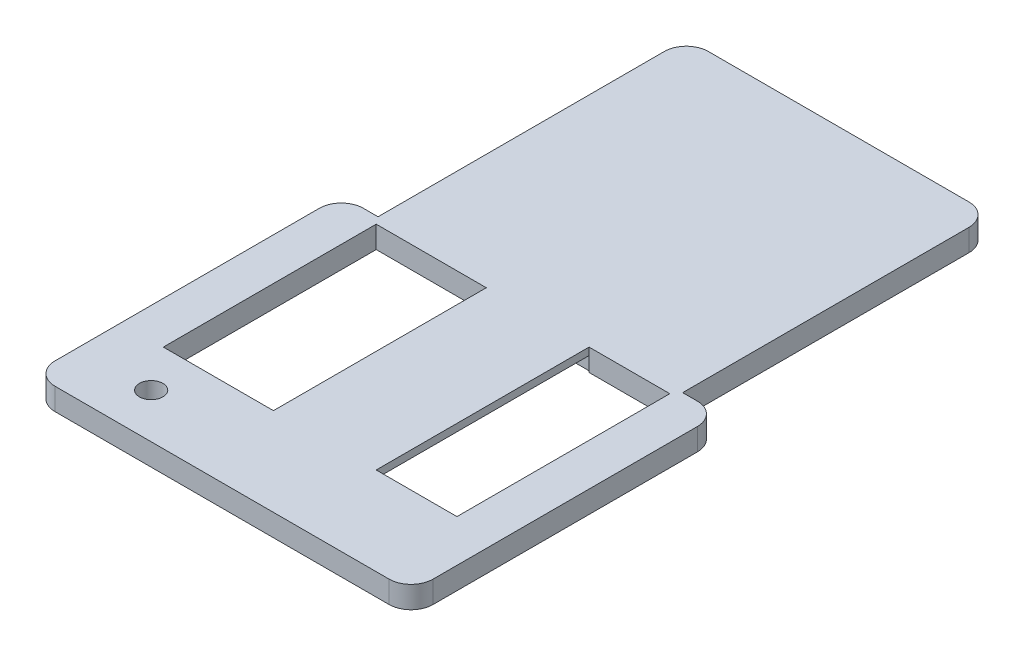
SolidWorks part; units mm, degrees
ref_plane "Front Plane" through (0, 0, 0) normal (0, 0, 1) x (1, 0, 0)
ref_plane "Top Plane" through (0, 0, 0) normal (0, 1, 0) x (1, 0, 0)
ref_plane "Right Plane" through (0, 0, 0) normal (1, 0, 0) x (0, 0, -1)
sketch "Sketch1" plane through (0, 0, 0) normal (0, 1, 0) x (1, 0, 0)
  line L0 (-20.75, 42) -> (-20.75, 0)
  line L1 (-20.75, 0) -> (-25.75, 0)
  line L2 (-25.75, 0) -> (-25.75, -42)
  line L3 (-25.75, -42) -> (25.75, -42)
  line L4 (25.75, -42) -> (25.75, 0)
  line L5 (25.75, 0) -> (20.75, 0)
  line L6 (20.75, 0) -> (20.75, 42)
  line L7 (20.75, 42) -> (-20.75, 42)
  line L8 (0, 42) -> (0, -42) construction
  dimension "D1" = 41.5
  dimension "D2" = 42
  dimension "D3" = 84
  dimension "D4" = 51.5
extrude "Boss-Extrude1" add sketch "Sketch1" along normal blind 3
fillet "Fillet1" radius 3 6 edges at (25.75, 1.5, 0) (25.75, 1.5, 42) (-25.75, 1.5, 42) (-25.75, 1.5, 0) (-20.75, 1.5, -42) (20.75, 1.5, -42)
sketch "Sketch2" plane through (0, 3, 0) normal (0, 1, 0) x (1, 0, 0)
  line L1 (-20, -1) -> (-5, -1)
  line L2 (-20, -1) -> (-20, -30)
  line L3 (-20, -30) -> (-5, -30)
  line L4 (-5, -1) -> (-5, -30)
  line L5 (-20, -1) -> (-5, -30) construction
  line L6 (-20, -30) -> (-5, -1) construction
  line L7 (20, -30) -> (9, -30)
  line L8 (20, -30) -> (20, -1)
  line L9 (20, -1) -> (9, -1)
  line L10 (9, -30) -> (9, -1)
  line L11 (20, -30) -> (9, -1) construction
  line L12 (20, -1) -> (9, -30) construction
  line L13 (-20, -15.5) -> (-25.75, -15.5) construction
  line L14 (-25.75, -3) -> (-25.75, -39) construction
  line L15 (20, -15.5) -> (25.75, -15.5) construction
  line L16 (25.75, -39) -> (25.75, -3) construction
  line L17 (-20.75, 0) -> (-22.75, 0) construction
  line L18 (-15.75, -30) -> (-15.75, -35.9074) construction
  line L19 (-15.75, -35.9074) -> (-15.75, -42) construction
  line L20 (-22.75, -42) -> (22.75, -42) construction
  line L21 (-25.75, -3) -> (-25.75, -39) construction
  circle A0 centre (-15.75, -35.9074) radius 1.6
  point P0 (-12.5, -15.5)
  point P5 (14.5, -15.5)
  point P22 (-21.75, 0)
  dimension "D6" = 3.2
  dimension "D1" = 29
  dimension "D2" = 15
  dimension "D3" = 11
  dimension "D4" = 1
  dimension "D5" = 14
  dimension "D7" = 10
extrude "Cut-Extrude1" cut sketch "Sketch2" against normal blind 3
sketch "Sketch3" plane through (0, 0, 0) normal (0, -1, 0) x (1, 0, 0)
  line L0 (10, -26) -> (10, -18)
  line L1 (10, -18) -> (2, -22)
  line L2 (2, -22) -> (10, -26)
  line L3 (-7, -22) -> (10, -22) construction
  line L4 (-4, -18) -> (-2, -18)
  line L5 (-4, -18) -> (-4, -26)
  line L6 (-4, -26) -> (-2, -26)
  line L7 (-2, -18) -> (-2, -26)
  line L8 (-4, -18) -> (-2, -26) construction
  line L9 (-4, -26) -> (-2, -18) construction
  line L10 (-8, -18) -> (-6, -18)
  line L11 (-8, -18) -> (-8, -26)
  line L12 (-8, -26) -> (-6, -26)
  line L13 (-6, -18) -> (-6, -26)
  line L14 (-8, -18) -> (-6, -26) construction
  line L15 (-8, -26) -> (-6, -18) construction
  line L16 (17.75, -42) -> (-17.75, -42) construction
  line L17 (0, -42) -> (0, -11.3286) construction
  point P2 (-3, -22)
  point P8 (-7, -22)
  dimension "D1" = 2
  dimension "D2" = 8
  dimension "D3" = 20
  dimension "D4" = 8
  dimension "D5" = 4
  dimension "D6" = 4
  dimension "D7" = 2
sketch "Sketch4" plane through (0, 0, 0) normal (0, -1, 0) x (1, 0, 0)
  line L0 (20, 1) -> (9, 1) construction
  line L1 (9, 30.2) -> (-5, 30.2)
  line L2 (9, 30.2) -> (9, 0.8)
  line L3 (9, 0.8) -> (-5, 0.8)
  line L4 (-5, 30.2) -> (-5, 0.8)
  line L5 (9, 30.2) -> (-5, 0.8) construction
  line L6 (9, 0.8) -> (-5, 30.2) construction
  line L7 (9, 30) -> (20, 30) construction
  line L8 (9, 1) -> (9, 30) construction
  line L9 (-5, 30) -> (-5, 1) construction
  point P0 (2, 15.5)
  dimension "D1" = 0.2
  dimension "D2" = 0.2
extrude "Cut-Extrude2" cut sketch "Sketch4" against normal blind 2
